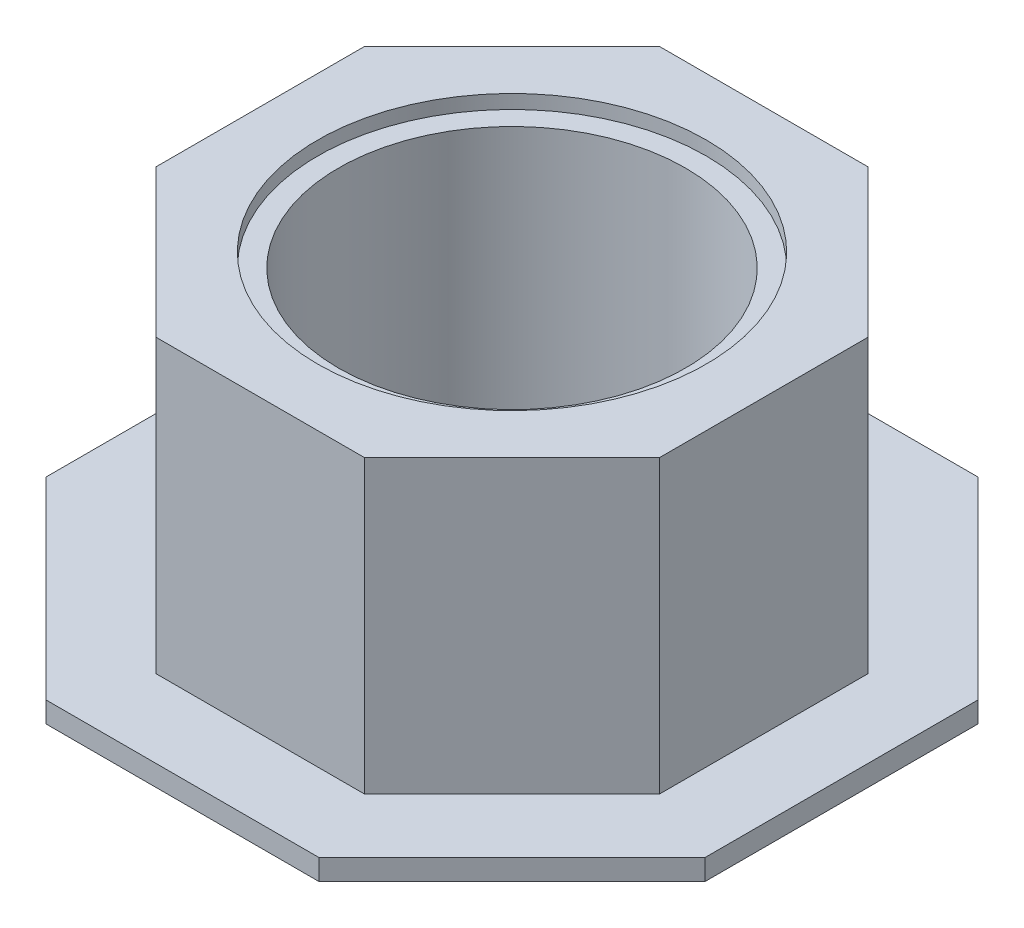
SolidWorks part; units mm, degrees
ref_plane "Front Plane" through (0, 0, 0) normal (0, 0, 1) x (1, 0, 0)
ref_plane "Top Plane" through (0, 0, 0) normal (0, 1, 0) x (1, 0, 0)
ref_plane "Right Plane" through (0, 0, 0) normal (1, 0, 0) x (0, 0, -1)
sketch "Sketch1" plane through (0, 0, 0) normal (0, 1, 0) x (1, 0, 0)
  line L1 (30.0678, -72.59) -> (72.59, -30.0678)
  line L2 (72.59, -30.0678) -> (72.59, 30.0678)
  line L3 (72.59, 30.0678) -> (30.0678, 72.59)
  line L4 (30.0678, 72.59) -> (-30.0678, 72.59)
  line L5 (-30.0678, 72.59) -> (-72.59, 30.0678)
  line L6 (-72.59, 30.0678) -> (-72.59, -30.0678)
  line L7 (-72.59, -30.0678) -> (-30.0678, -72.59)
  line L8 (-30.0678, -72.59) -> (30.0678, -72.59)
  line L9 (39.3959, -95.11) -> (95.11, -39.3959)
  line L10 (95.11, -39.3959) -> (95.11, 39.3959)
  line L11 (95.11, 39.3959) -> (39.3959, 95.11)
  line L12 (39.3959, 95.11) -> (-39.3959, 95.11)
  line L13 (-39.3959, 95.11) -> (-95.11, 39.3959)
  line L14 (-95.11, 39.3959) -> (-95.11, -39.3959)
  line L15 (-95.11, -39.3959) -> (-39.3959, -95.11)
  line L16 (-39.3959, -95.11) -> (39.3959, -95.11)
  circle A0 centre (0, 0) radius 72.59 construction
  circle A1 centre (0, 0) radius 95.11 construction
  circle A3 centre (0, 0) radius 50
  dimension "D5" = 100
  dimension "D1" = 72.59
  dimension "D2" = 95.11
  dimension "D3" = 60.1355
sketch "Sketch2" plane through (0, 0, 0) normal (0, 1, 0) x (1, 0, 0)
  line L1 (39.35, -94.9993) -> (94.9993, -39.35)
  line L2 (94.9993, -39.35) -> (94.9993, 39.35)
  line L3 (94.9993, 39.35) -> (39.35, 94.9993)
  line L4 (39.35, 94.9993) -> (-39.35, 94.9993)
  line L5 (-39.35, 94.9993) -> (-94.9993, 39.35)
  line L6 (-94.9993, 39.35) -> (-94.9993, -39.35)
  line L7 (-94.9993, -39.35) -> (-39.35, -94.9993)
  line L8 (-39.35, -94.9993) -> (39.35, -94.9993)
  circle A0 centre (0, 0) radius 94.9993 construction
  dimension "D1" = 78.7
extrude "Boss-Extrude7" add sketch "Sketch2" against normal blind 6
extrude "Boss-Extrude8" add sketch "Sketch1" along normal blind 84 contours L7 L8 L1 L2 L3 L4 L5 L6 A3
sketch "Sketch4" plane through (0, 84, 0) normal (0, 1, 0) x (1, 0, 0)
  circle A0 centre (0, 0) radius 56
  circle A1 centre (0, 0) radius 50
extrude "Cut-Extrude1" cut sketch "Sketch4" against normal blind 4
ref_point "Point1"
